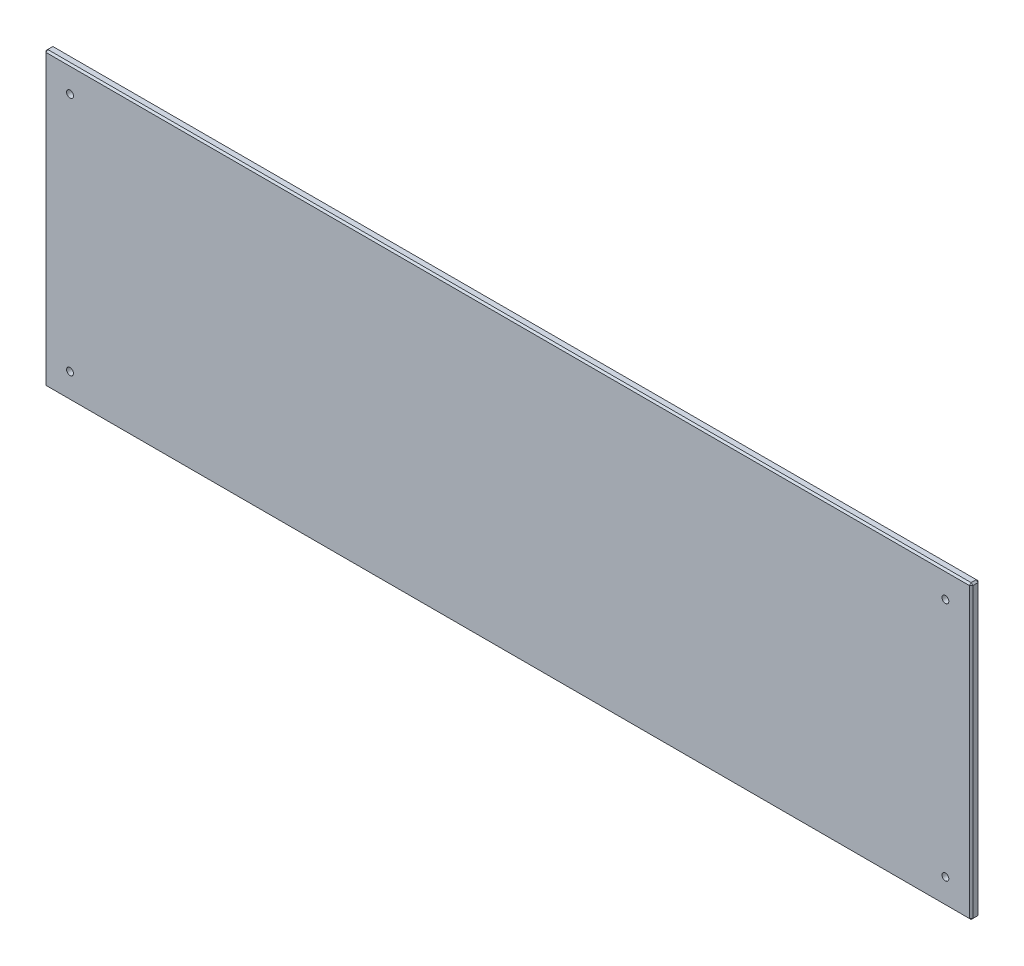
SolidWorks part; units mm, degrees
material "ABS"
ref_plane "Front Plane" through (0, 0, 0) normal (0, 0, 1) x (1, 0, 0)
ref_plane "Top Plane" through (0, 0, 0) normal (0, 1, 0) x (1, 0, 0)
ref_plane "Right Plane" through (0, 0, 0) normal (1, 0, 0) x (0, 0, -1)
sketch "Sketch1" plane through (0, 0, 0) normal (0, 0, 1) x (1, 0, 0)
  line L1 (0, 0) -> (540, 0)
  line L2 (0, 0) -> (0, 170)
  line L3 (0, 170) -> (540, 170)
  line L4 (540, 0) -> (540, 170)
  dimension "D1" = 540
  dimension "D2" = 170
extrude "Boss-Extrude1" add sketch "Sketch1" along normal blind 5
chamfer "Chamfer1" distance 1 angle 45 12 edges at (270, 0, 0) (540, 85, 0) (270, 170, 0) (0, 85, 0) (270, 170, 5) (0, 170, 2.5) (0, 85, 5) (0, 0, 2.5) (270, 0, 5) (540, 0, 2.5) (540, 85, 5) (540, 170, 2.5)
sketch "Sketch2" plane through (0, 0, 5) normal (0, 0, 1) x (1, 0, 0)
  line L0 (1, 170) -> (539, 170) construction
  line L1 (15, 155) -> (525, 155) construction
  line L2 (15, 155) -> (15, 15) construction
  line L3 (15, 15) -> (525, 15) construction
  line L4 (525, 155) -> (525, 15) construction
  line L5 (540, 169) -> (540, 1) construction
  line L6 (539, 0) -> (1, 0) construction
  line L7 (0, 1) -> (0, 169) construction
  circle A0 centre (525, 155) radius 2
  circle A1 centre (525, 15) radius 2
  circle A2 centre (15, 155) radius 2
  circle A3 centre (15, 15) radius 2
  dimension "D5" = 4
  dimension "D6" = 4
  dimension "D7" = 4
  dimension "D8" = 4
  dimension "D1" = 15
  dimension "D2" = 15
  dimension "D3" = 15
  dimension "D4" = 15
extrude "Cut-Extrude1" cut sketch "Sketch2" against normal blind 5
